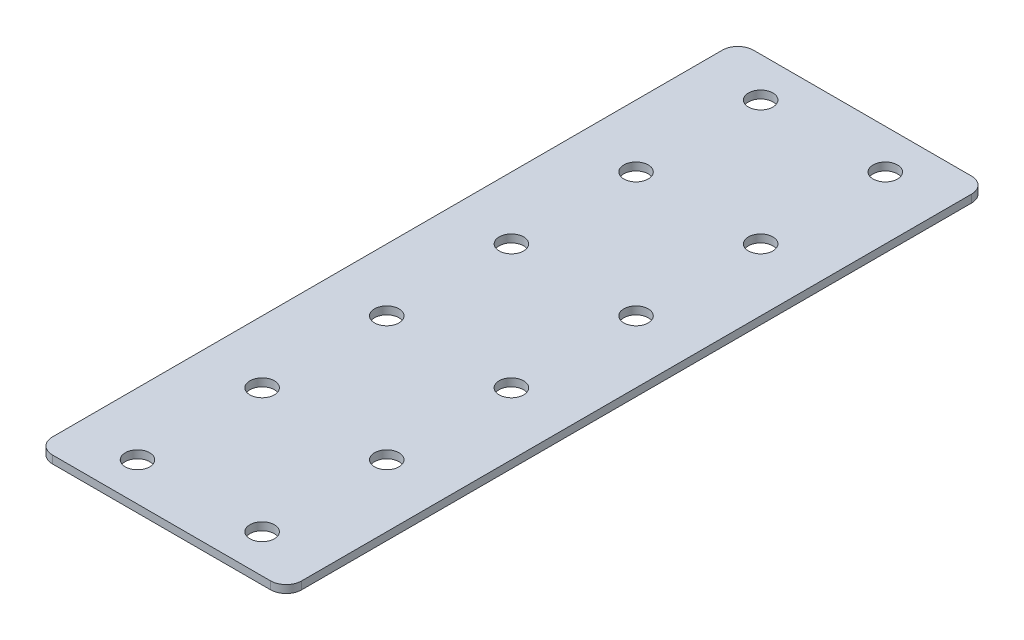
SolidWorks part; units mm, degrees
material "6061-T6 (SS)"
ref_plane "Front Plane" through (0, 0, 0) normal (0, 0, 1) x (1, 0, 0)
ref_plane "Top Plane" through (0, 0, 0) normal (0, 1, 0) x (1, 0, 0)
ref_plane "Right Plane" through (0, 0, 0) normal (1, 0, 0) x (0, 0, -1)
sketch "Sketch1" plane through (0, 0, 0) normal (0, 1, 0) x (1, 0, 0)
  line L1 (0, 0) -> (50.8, 0)
  line L2 (0, 0) -> (0, 142.875)
  line L3 (0, 142.875) -> (50.8, 142.875)
  line L4 (50.8, 0) -> (50.8, 142.875)
  circle A0 centre (12.7, 7.8133) radius 2.4892
  circle A1 centre (12.7, 33.2133) radius 2.4892
  circle A2 centre (12.7, 58.6133) radius 2.4892
  circle A3 centre (12.7, 84.0133) radius 2.4892
  circle A4 centre (12.7, 109.4133) radius 2.4892
  circle A5 centre (12.7, 134.8133) radius 2.4892
  circle A6 centre (38.1, 33.2133) radius 2.4892
  circle A7 centre (38.1, 58.6133) radius 2.4892
  circle A8 centre (38.1, 84.0133) radius 2.4892
  circle A9 centre (38.1, 109.4133) radius 2.4892
  circle A10 centre (38.1, 134.8133) radius 2.4892
  circle A11 centre (38.1, 7.8133) radius 2.4892
  point P7 (37.1383, 0)
  dimension "D3" = 4.9784
  dimension "D4" = 12.7
  dimension "D5" = 7.8133
  dimension "D1" = 50.8
  dimension "D2" = 142.875
  dimension "D8" = 25.4
  dimension "D9" = 25.4
  dimension "D6" = 6
  dimension "D7" = 2
extrude "Boss-Extrude1" add sketch "Sketch1" along normal blind 1.5875
fillet "Fillet1" radius 3.175 4 edges at (0, 0.7937, -142.875) (50.8, 0.7937, -142.875) (0, 0.7937, 0) (50.8, 0.7937, 0)
